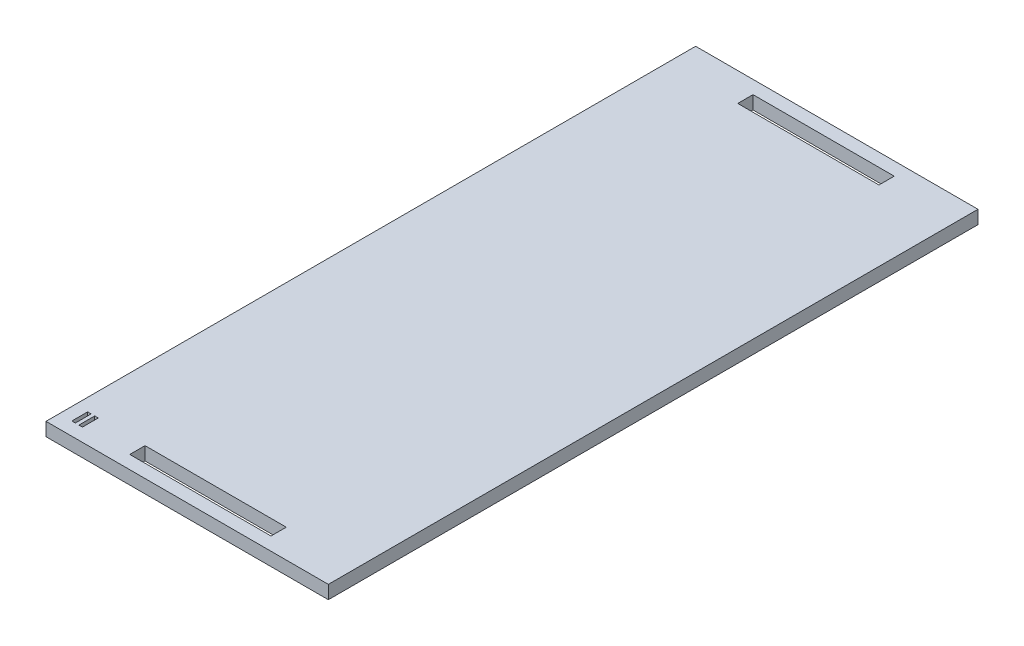
SolidWorks part; units mm, degrees
ref_plane "Front Plane" through (0, 0, 0) normal (0, 0, 1) x (1, 0, 0)
ref_plane "Top Plane" through (0, 0, 0) normal (0, 1, 0) x (1, 0, 0)
ref_plane "Right Plane" through (0, 0, 0) normal (1, 0, 0) x (0, 0, -1)
sketch "Sketch1" plane through (0, 0, 0) normal (0, 1, 0) x (1, 0, 0)
  line L0 (-31.7373, 66.4972) -> (31.7373, 66.4972) construction
  line L1 (31.7373, -73.025) -> (-31.7373, -73.025)
  line L2 (31.7373, -73.025) -> (31.7373, 73.025)
  line L3 (31.7373, 73.025) -> (-31.7373, 73.025)
  line L4 (-31.7373, -73.025) -> (-31.7373, 73.025)
  line L5 (31.7373, -73.025) -> (-31.7373, 73.025) construction
  line L6 (31.7373, 73.025) -> (-31.7373, -73.025) construction
  line L7 (-31.7373, -66.4972) -> (31.7373, -66.4972) construction
  line L8 (-31.7373, 66.4972) -> (-31.7373, -66.4972) construction
  line L9 (31.7373, 66.4972) -> (31.7373, -66.4972) construction
  line L10 (0, 66.6242) -> (0, -66.6242) construction
  line L11 (-15.875, 70.0532) -> (15.875, 70.0532)
  line L12 (-15.875, 70.0532) -> (-15.875, 66.6242)
  line L13 (-15.875, 66.6242) -> (15.875, 66.6242)
  line L14 (15.875, 70.0532) -> (15.875, 66.6242)
  line L15 (-15.875, -66.6242) -> (15.875, -66.6242)
  line L16 (-15.875, -66.6242) -> (-15.875, -70.0532)
  line L17 (-15.875, -70.0532) -> (15.875, -70.0532)
  line L18 (15.875, -66.6242) -> (15.875, -70.0532)
  line L19 (-31.7373, -70.0532) -> (31.7373, -70.0532) construction
  line L20 (-28.1065, -68.2752) -> (-27.3128, -68.2752) construction
  line L21 (-28.9003, -66.4972) -> (-28.1065, -66.4972)
  line L22 (-28.9003, -66.4972) -> (-28.9003, -70.0532)
  line L23 (-28.9003, -70.0532) -> (-28.1065, -70.0532)
  line L24 (-28.1065, -66.4972) -> (-28.1065, -70.0532)
  line L25 (-27.3128, -70.0532) -> (-26.519, -70.0532)
  line L26 (-27.3128, -70.0532) -> (-27.3128, -66.4972)
  line L27 (-27.3128, -66.4972) -> (-26.519, -66.4972)
  line L28 (-26.519, -70.0532) -> (-26.519, -66.4972)
  point P0 (0, 0)
  point P10 (31.7373, 0)
  point P11 (31.7373, 0)
  point P16 (0, 66.6242)
  point P17 (0, 0)
  dimension "D1" = 63.4746
  dimension "D2" = 146.05
  dimension "D3" = 132.9944
  dimension "D4" = 3.429
  dimension "D5" = 31.75
  dimension "D6" = 0.254
  dimension "D7" = 0.7937
extrude "Boss-Extrude1" add sketch "Sketch1" along normal blind 2.9972 contours L4 L1 L2 L3 L11 L14 L13 L12 L15 L18 L17 L16
